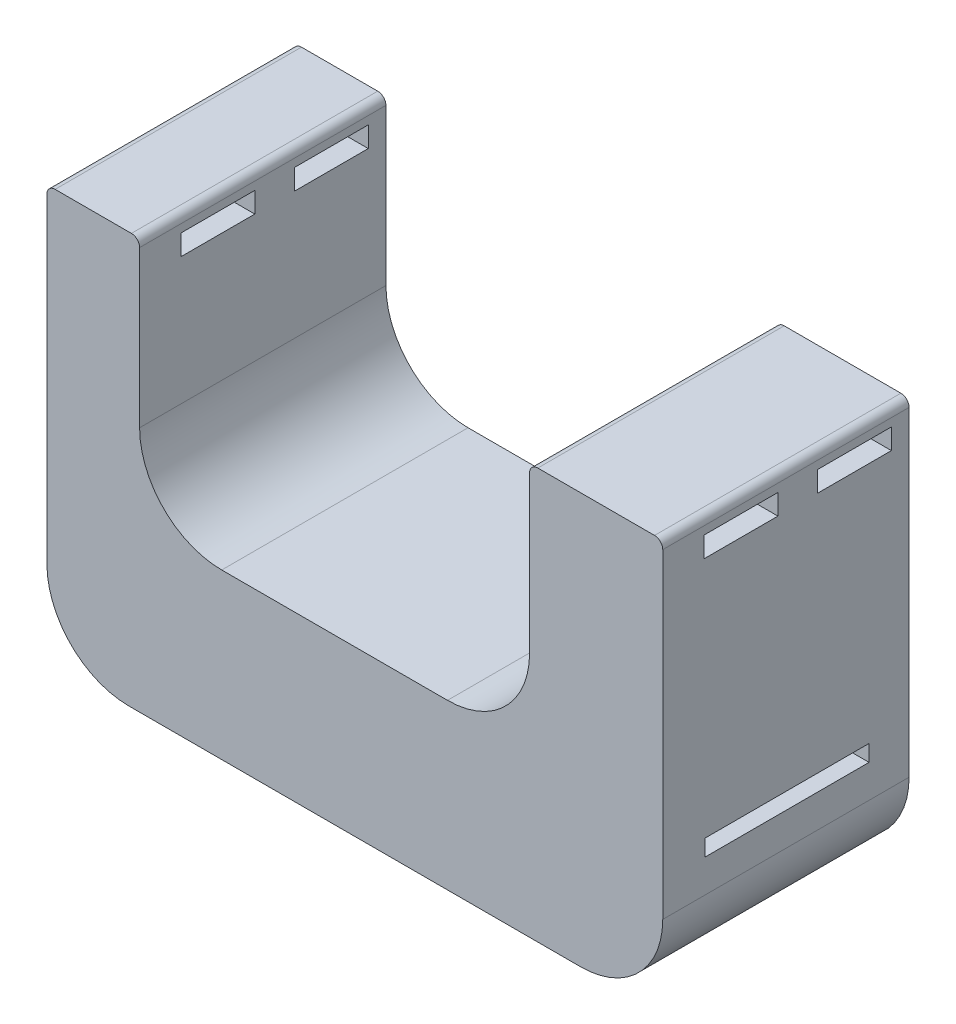
SolidWorks part; units mm, degrees
ref_plane "Front Plane" through (0, 0, 0) normal (0, 0, 1) x (1, 0, 0)
ref_plane "Top Plane" through (0, 0, 0) normal (0, 1, 0) x (1, 0, 0)
ref_plane "Right Plane" through (0, 0, 0) normal (1, 0, 0) x (0, 0, -1)
sketch "Sketch1" plane through (0, 0, 0) normal (0, 1, 0) x (1, 0, 0)
  line L0 (-86.3127, 34.4463) -> (104.1873, 34.4463)
  line L1 (104.1873, 34.4463) -> (104.1873, -41.7537)
  line L2 (104.1873, -41.7537) -> (-86.3127, -41.7537)
  line L3 (-86.3127, -41.7537) -> (-86.3127, 34.4463)
  dimension "D1" = 190.5
  dimension "D2" = 76.2
extrude "Boss-Extrude1" add sketch "Sketch1" against normal blind 50.8
sketch "Sketch2" plane through (0, 0, 0) normal (0, 1, 0) x (1, 0, 0)
  line L0 (-86.3127, -41.7537) -> (-57.639, -41.7537)
  line L1 (-86.3127, -41.7537) -> (104.1873, -41.7537) construction
  line L2 (-57.639, -41.7537) -> (-57.639, 34.4463)
  line L3 (104.1873, 34.4463) -> (-86.3127, 34.4463) construction
  line L4 (-57.639, 34.4463) -> (-86.3127, 34.4463)
  line L5 (-86.3127, 34.4463) -> (-86.3127, -41.7537)
  line L6 (104.1873, 34.4463) -> (63.003, 34.4463)
  line L7 (63.003, 34.4463) -> (63.003, -41.7537)
  line L8 (63.003, -41.7537) -> (104.1873, -41.7537)
  line L9 (104.1873, -41.7537) -> (104.1873, 34.4463)
extrude "Boss-Extrude2" add sketch "Sketch2" along normal blind 76.2
fillet "Fillet1" radius 25.4 4 edges at (-57.639, 0, 3.6537) (63.003, 0, 3.6537) (-86.3127, -50.8, 3.6537) (104.1873, -50.8, 3.6537)
sketch "Sketch4" plane through (-86.3127, 0, 0) normal (-1, 0, 0) x (0, 0, 1)
  line L0 (-28.9788, 71.1752) -> (-28.9788, 64.8252)
  line L1 (-28.9788, 64.8252) -> (-6.1188, 64.8252)
  line L2 (-6.1188, 64.8252) -> (-6.1188, 71.1752)
  line L3 (-6.1188, 71.1752) -> (-28.9788, 71.1752)
  dimension "D1" = 6.35
  dimension "D2" = 22.86
extrude "Cut-Extrude1" cut sketch "Sketch4" against normal through all both and the other way through all
mirror "Mirror1" about plane through (0, 0, 0) normal (0, 0, 1) of "Cut-Extrude1"
fillet "Fillet2" radius 2.54 4 edges at (104.1873, 76.2, 3.6537) (63.003, 76.2, 3.6537) (-57.639, 76.2, 3.6537) (-86.3127, 76.2, 3.6537)
sketch "Sketch5" plane through (0, -50.8, 0) normal (0, -1, 0) x (1, 0, 0)
  line L0 (-25.1374, 33.9615) -> (-25.1374, -26.9985)
  line L1 (-25.1374, -26.9985) -> (38.3626, -26.9985)
  line L2 (38.3626, -26.9985) -> (38.3626, 33.9615)
  line L3 (38.3626, 33.9615) -> (-25.1374, 33.9615)
  dimension "D1" = 60.96
  dimension "D2" = 63.5
extrude "Cut-Extrude3" cut sketch "Sketch5" against normal blind 40.64
sketch "Sketch7" plane through (38.3626, 0, 0) normal (-1, 0, 0) x (0, 0, 1)
  line L0 (-22.0702, -10.16) -> (-22.0702, -15.24)
  line L1 (-26.9985, -10.16) -> (33.9615, -10.16) construction
  line L2 (-22.0702, -15.24) -> (28.7298, -15.24)
  line L3 (28.7298, -15.24) -> (28.7298, -10.16)
  line L4 (28.7298, -10.16) -> (-22.0702, -10.16)
  dimension "D1" = 50.8
  dimension "D2" = 5.08
extrude "Cut-Extrude4" cut sketch "Sketch7" against normal blind 76.2
